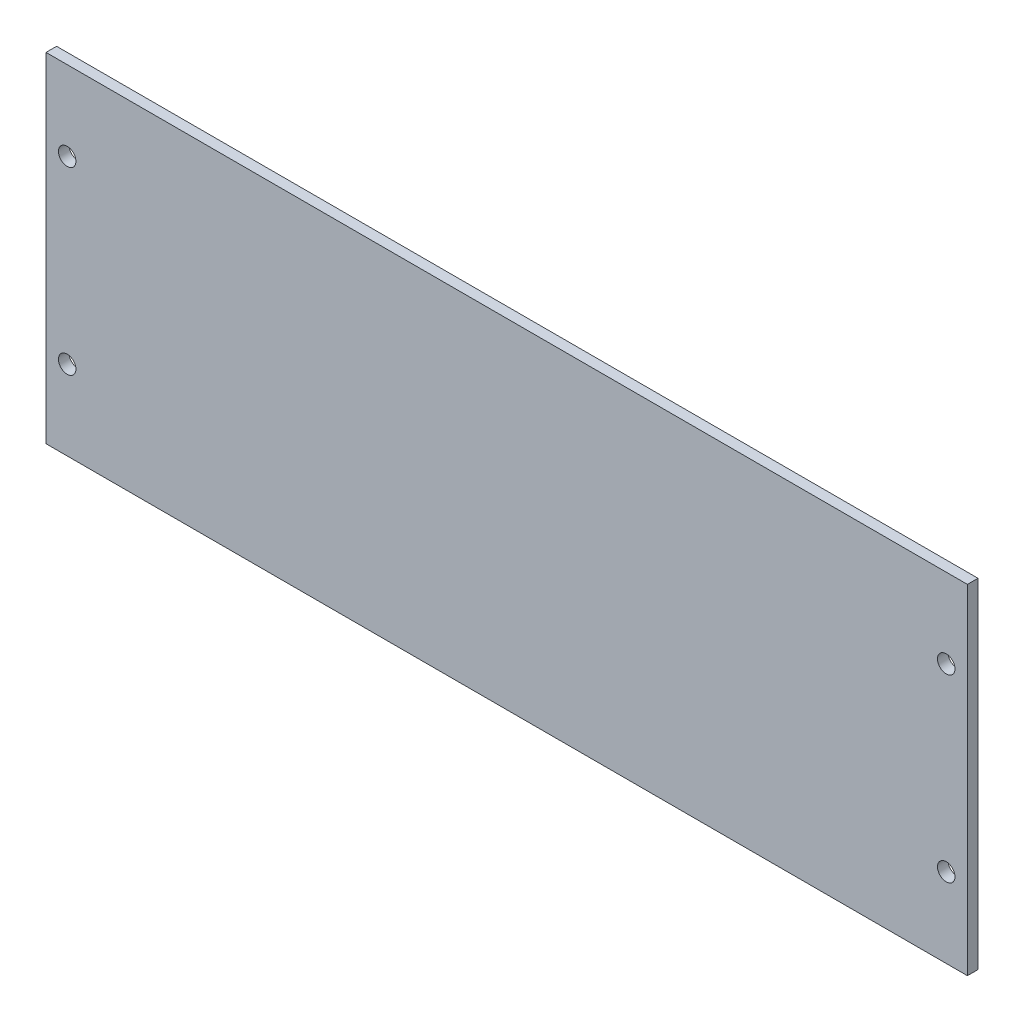
SolidWorks part; units mm, degrees
ref_plane "Plan de face" through (0, 0, 0) normal (0, 0, 1) x (1, 0, 0)
ref_plane "Plan de dessus" through (0, 0, 0) normal (0, 1, 0) x (1, 0, 0)
ref_plane "Plan de droite" through (0, 0, 0) normal (1, 0, 0) x (0, 0, -1)
sketch "Esquisse1" plane through (0, 0, 0) normal (0, 0, 1) x (1, 0, 0)
  line L1 (-174, -64) -> (174, -64)
  line L2 (-174, -64) -> (-174, 64)
  line L3 (-174, 64) -> (174, 64)
  line L4 (174, -64) -> (174, 64)
  line L5 (-174, -64) -> (174, 64) construction
  line L6 (-174, 64) -> (174, -64) construction
  point P0 (0, 0)
  dimension "D1" = 348
  dimension "D2" = 128
extrude "Boss.-Extru.1" add sketch "Esquisse1" along normal blind 4
hole_wizard "Dégagement M61" positions "Esquisse3" profile "Esquisse2" hole size "M6" standard "ISO" end condition through all
sketch "Esquisse3" plane through (0, 0, 0) normal (0, 0, -1) x (-1, 0, 0)
  line L1 (-166, -56) -> (166, -56) construction
  line L2 (-166, -56) -> (-166, 56) construction
  line L3 (-166, 56) -> (166, 56) construction
  line L4 (166, -56) -> (166, 56) construction
  line L5 (-166, -56) -> (166, 56) construction
  line L6 (-166, 56) -> (166, -56) construction
  line L7 (-174, 64) -> (174, 64) construction
  line L9 (0, 153.0002) -> (0, -160.7922) construction
  line L11 (-248.73, 0) -> (316.3802, 0) construction
  line L12 (174, 64) -> (174, -64) construction
  line L13 (174, -64) -> (-174, -64) construction
  point P6 (166, 34)
  point P8 (-166, 34)
  point P156 (166, -34)
  point P158 (-166, -34)
  dimension "D1" = 8
  dimension "D4" = 8
  dimension "D5" = 8
  dimension "D6" = 30
sketch "Esquisse2" plane through (-166, 34, 0) normal (1, 0, 0) x (0, 1, 0)
  line L0 (0, 0) -> (0, 4)
  line L1 (0, 4) -> (3.3, 4)
  line L2 (3.3, 4) -> (3.3, 0)
  line L5 (3.3, 0) -> (0, 0)
  line L11 (0, -6.35) -> (0, 107.95) construction
  dimension "Diamètre du perçage jusqu'au prochain" = 6.6
  dimension "Profondeur du perçage jusqu'au prochain" = 4
